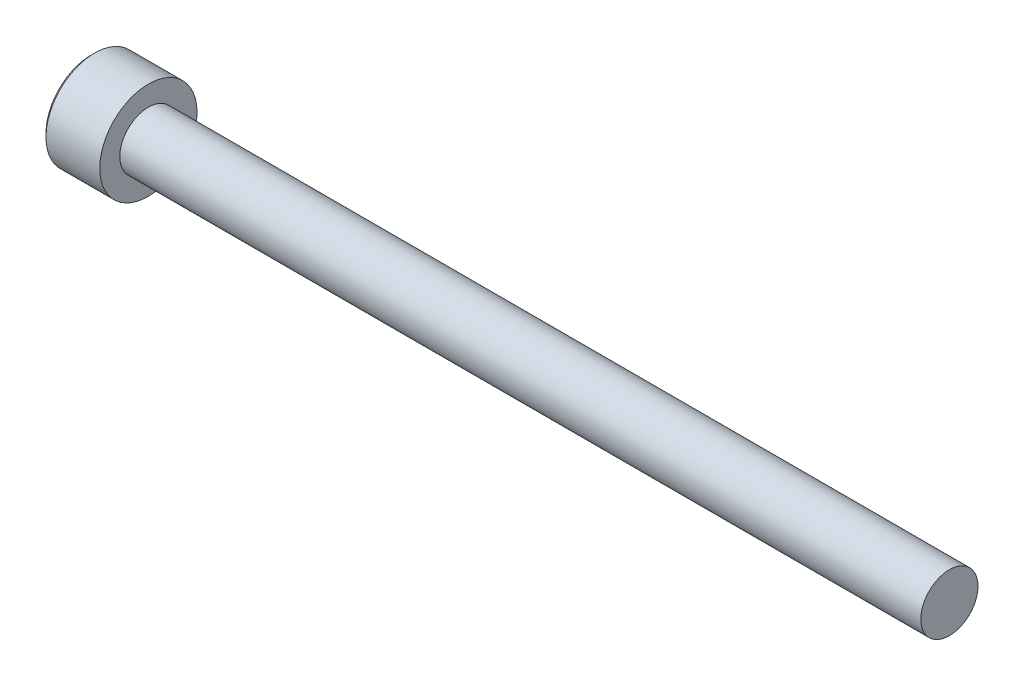
SolidWorks part; units mm, degrees
ref_plane "Front Plane" through (0, 0, 0) normal (0, 0, 1) x (1, 0, 0)
ref_plane "Top Plane" through (0, 0, 0) normal (0, 1, 0) x (1, 0, 0)
ref_plane "Right Plane" through (0, 0, 0) normal (1, 0, 0) x (0, 0, -1)
sketch "Sketch1" plane through (0, 0, 0) normal (0, 0, 1) x (1, 0, 0)
  line L0 (-5, 0) -> (70, 0) construction
  line L1 (-5, 0) -> (-5, 3.95)
  line L2 (-4.7, 4.25) -> (0, 4.25)
  line L3 (0, 4.25) -> (0, 2.5)
  line L4 (0, 2.5) -> (70, 2.5)
  line L5 (70, 2.5) -> (70, 0)
  line L6 (70, 0) -> (-5, 0)
  line L7 (-5, 3.95) -> (-4.7, 4.25)
  point P4 (-5, 4.25)
  dimension "FIX_4" = 8.5
  dimension "FIX_5" = 5
  dimension "FIX_1" = 5
  dimension "FIX_2" = 70
revolve "Revolve1" add sketch "Sketch1" about L0
cosmetic thread "Thread201" parameters "NFIX_1"=4.134
sketch "Sketch2" plane through (-5, 0, 0) normal (-1, 0, 0) x (0, 0, 1)
  line L1 (0, 2.3094) -> (-2, 1.1547)
  line L2 (-2, 1.1547) -> (-2, -1.1547)
  line L3 (-2, -1.1547) -> (0, -2.3094)
  line L4 (0, -2.3094) -> (2, -1.1547)
  line L5 (2, -1.1547) -> (2, 1.1547)
  line L6 (2, 1.1547) -> (0, 2.3094)
  circle A0 centre (0, 0) radius 2 construction
extrude "Cut-Extrude1" cut sketch "Sketch2" against normal blind 2.5
sketch "Sketch3" plane through (0, 0, 0) normal (0, 0, 1) x (1, 0, 0)
  line L0 (-2.5, 0) -> (-1.2983, 0) construction
  line L1 (-2.5, 0) -> (-2.5, 2)
  line L2 (-2.5, 2) -> (-1.2983, 0)
  line L3 (-1.2983, 0) -> (-2.5, 0)
  line L4 (-2.5, 1.1547) -> (-2.5, -1.1547) construction
  dimension "FIX_9" = 59
revolve "Cut-Revolve1" cut sketch "Sketch3" about L0
